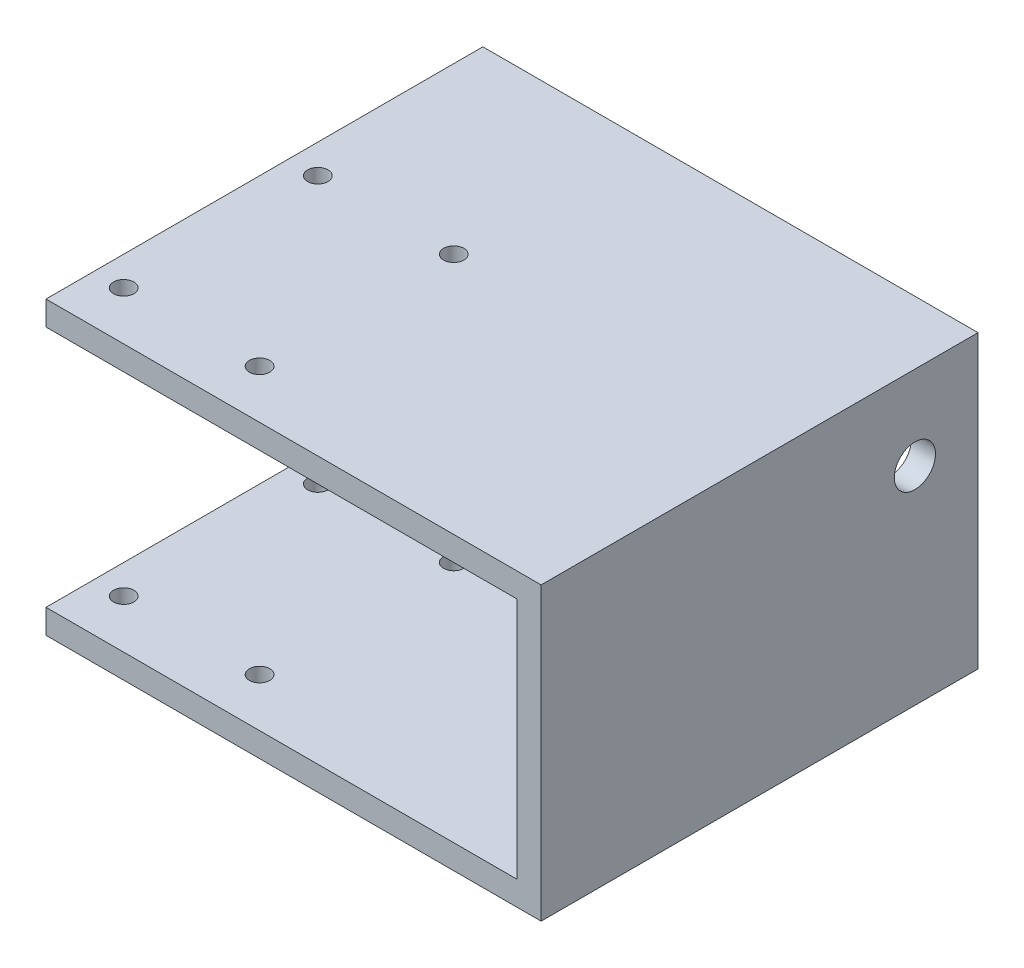
SolidWorks part; units mm, degrees
ref_plane "前视基准面" through (0, 0, 0) normal (0, 0, 1) x (1, 0, 0)
ref_plane "上视基准面" through (0, 0, 0) normal (0, 1, 0) x (1, 0, 0)
ref_plane "右视基准面" through (0, 0, 0) normal (1, 0, 0) x (0, 0, -1)
other "Configuration Table"
sketch "草图1" plane through (0, 0, 0) normal (0, 0, 1) x (1, 0, 0)
  line L0 (0, 0) -> (0, 5)
  line L1 (0, 5) -> (102, 5)
  line L2 (102, 5) -> (102, -55)
  line L3 (102, -55) -> (0, -55)
  line L4 (0, -55) -> (0, -50)
  line L5 (0, -50) -> (97, -50)
  line L6 (97, -50) -> (97, 0)
  line L7 (97, 0) -> (0, 0)
  dimension "D1" = 5
  dimension "D2" = 97
  dimension "D3" = 5
  dimension "D4" = 5
  dimension "D5" = 50
extrude "凸台-拉伸1" add sketch "草图1" along normal blind 90 contours L5 L6 L7 L0 L1 L2 L3 L4
sketch "Sketch1" plane through (0, 0, 0) normal (0, 1, 0) x (1, 0, 0)
  line L0 (0, -90) -> (0, 0) construction
  line L1 (6, -40) -> (34, -40) construction
  line L2 (6, -40) -> (6, -80) construction
  line L3 (6, -80) -> (34, -80) construction
  line L4 (34, -40) -> (34, -80) construction
  line L5 (0, 0) -> (102, -90) construction
  line L6 (102, 0) -> (0, -90) construction
  line L7 (51, -45) -> (87.6415, -45) construction
  line L8 (0, 0) -> (102, 0) construction
  line L9 (0, -90) -> (102, -90) construction
  circle A0 centre (6, -40) radius 2.1
  circle A1 centre (34, -40) radius 2.1
  circle A2 centre (34, -80) radius 2.1
  circle A3 centre (6, -80) radius 2.1
  point P18 (51, -45)
  dimension "D5" = 4.2
  dimension "D6" = 4.2
  dimension "D7" = 4.2
  dimension "D8" = 4.2
  dimension "D1" = 6
  dimension "D2" = 28
  dimension "D3" = 40
  dimension "D4" = 10
extrude "Cut-Extrude1" cut sketch "Sketch1" along normal through all both and the other way through all
sketch "草图2" plane through (97, 0, 0) normal (-1, 0, 0) x (0, 0, 1)
  line L0 (90, 0) -> (0, 0) construction
  line L1 (90, -50) -> (90, 0) construction
  line L2 (45, 0) -> (45, -50) construction
  line L3 (90, -50) -> (0, -50) construction
  line L4 (90, 0) -> (0, 0) construction
  circle A0 centre (77, -12.25) radius 12.25
  circle A1 centre (77, -12.25) radius 7
  circle A2 centre (13, -12.25) radius 7
  circle A3 centre (13, -12.25) radius 4.25
  point P16 (45, 0)
  dimension "D1" = 24.5
  dimension "D2" = 14
  dimension "D5" = 8.5
  dimension "D3" = 12.25
  dimension "D4" = 13
extrude "切除-拉伸1" cut sketch "草图2" against normal through all contours A3
